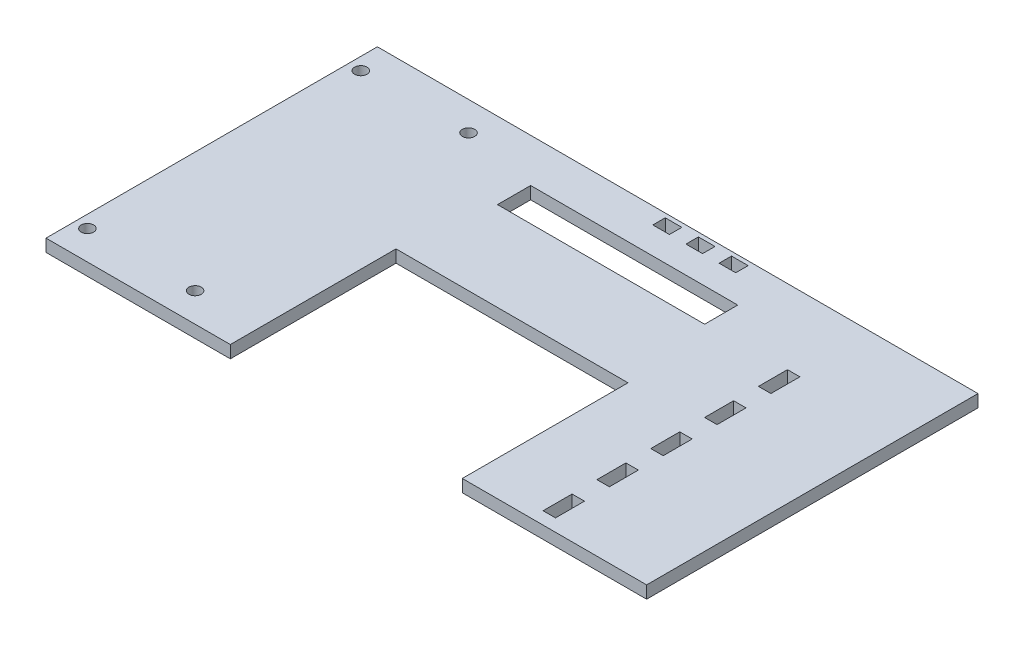
SolidWorks part; units mm, degrees
ref_plane "Front Plane" through (0, 0, 0) normal (0, 0, 1) x (1, 0, 0)
ref_plane "Top Plane" through (0, 0, 0) normal (0, 1, 0) x (1, 0, 0)
ref_plane "Right Plane" through (0, 0, 0) normal (1, 0, 0) x (0, 0, -1)
sketch "Sketch1" plane through (0, 0, 0) normal (0, 1, 0) x (1, 0, 0)
  line L0 (44.5, 9) -> (44.5, 2)
  line L1 (-72.5, -40) -> (-28, -40)
  line L2 (-72.5, -40) -> (-72.5, 40)
  line L3 (-72.5, 40) -> (72.5, 40)
  line L4 (72.5, -40) -> (72.5, 40)
  line L5 (-72.5, -40) -> (72.5, 40) construction
  line L6 (-72.5, 40) -> (72.5, -40) construction
  line L7 (44.5, 22) -> (47.5, 22)
  line L8 (44.5, 22) -> (44.5, 15)
  line L9 (44.5, 15) -> (47.5, 15)
  line L10 (47.5, 22) -> (47.5, 15)
  line L11 (44.5, 22) -> (47.5, 15) construction
  line L12 (44.5, 15) -> (47.5, 22) construction
  line L13 (44.5, 9) -> (47.5, 9)
  line L14 (47.5, 9) -> (47.5, 2)
  line L15 (44.5, 2) -> (47.5, 2)
  line L16 (44.5, -4) -> (44.5, -11)
  line L17 (44.5, -4) -> (47.5, -4)
  line L18 (47.5, -4) -> (47.5, -11)
  line L19 (44.5, -11) -> (47.5, -11)
  line L20 (44.5, -17) -> (44.5, -24)
  line L21 (44.5, -17) -> (47.5, -17)
  line L22 (47.5, -17) -> (47.5, -24)
  line L23 (44.5, -24) -> (47.5, -24)
  line L24 (44.5, -30) -> (44.5, -37)
  line L25 (44.5, -30) -> (47.5, -30)
  line L26 (47.5, -30) -> (47.5, -37)
  line L27 (44.5, -37) -> (47.5, -37)
  line L28 (-28, -40) -> (-28, 0)
  line L29 (-2, 39) -> (2, 39)
  line L30 (-2, 39) -> (-2, 36)
  line L31 (-2, 36) -> (2, 36)
  line L32 (2, 39) -> (2, 36)
  line L33 (-2, 39) -> (2, 36) construction
  line L34 (-2, 36) -> (2, 39) construction
  line L35 (0, 0) -> (9.2735, 0) construction
  line L36 (-28, 0) -> (28, 0)
  line L37 (28, 0) -> (28, -40)
  line L38 (28, -40) -> (72.5, -40)
  line L40 (6, 39) -> (10, 39)
  line L41 (6, 39) -> (6, 36)
  line L42 (6, 36) -> (10, 36)
  line L43 (10, 39) -> (10, 36)
  line L44 (0, 37.5) -> (0, 38.6806) construction
  line L45 (14, 39) -> (18, 39)
  line L46 (14, 39) -> (14, 36)
  line L47 (14, 36) -> (18, 36)
  line L48 (18, 39) -> (18, 36)
  circle A0 centre (-69.5, 33) radius 1.5
  circle A1 centre (-43.5, 33) radius 1.5
  circle A2 centre (-43.5, -33) radius 1.5
  circle A3 centre (-69.5, -33) radius 1.5
  point P0 (0, 0)
  point P11 (0, 37.5)
  point P32 (0, 0)
  point P57 (0, 0)
  dimension "D10" = 3
  dimension "D1" = 145
  dimension "D2" = 80
  dimension "D3" = 4
  dimension "D4" = 7
  dimension "D5" = 3
  dimension "D7" = 6
  dimension "D8" = 3
  dimension "D9" = 1
  dimension "D11" = 26
  dimension "D12" = 66
  dimension "D13" = 7
  dimension "D14" = 3
  dimension "D16" = 25
  dimension "D17" = 56
  dimension "D18" = 40
  dimension "D19" = 3
  dimension "D6" = 5
  dimension "D15" = 3
extrude "Boss-Extrude1" add sketch "Sketch1" along normal blind 3
sketch "Sketch5" plane through (0, 0, 0) normal (0, -1, 0) x (1, 0, 0)
  line L0 (72.5, -40) -> (-72.5, -40) construction
  line L1 (25, -21.5) -> (-25, -21.5)
  line L2 (25, -21.5) -> (25, -29.5)
  line L3 (25, -29.5) -> (-25, -29.5)
  line L4 (-25, -21.5) -> (-25, -29.5)
  line L5 (72.5, 40) -> (72.5, -40) construction
  dimension "D1" = 8
  dimension "D2" = 50
  dimension "D3" = 10.5
  dimension "D4" = 47.5
extrude "Cut-Extrude1" cut sketch "Sketch5" against normal blind 10
